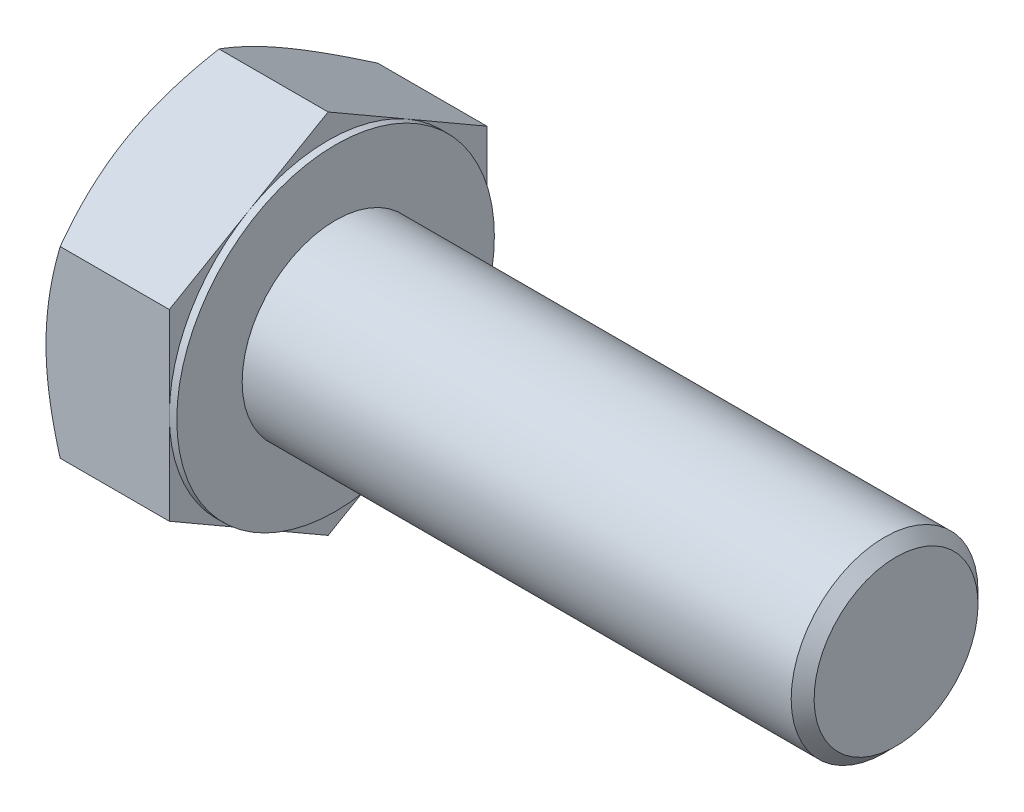
SolidWorks part; units mm, degrees
ref_plane "前基準面" through (0, 0, 0) normal (0, 0, 1) x (1, 0, 0)
ref_plane "上基準面" through (0, 0, 0) normal (0, 1, 0) x (1, 0, 0)
ref_plane "右基準面" through (0, 0, 0) normal (1, 0, 0) x (0, 0, -1)
ref_plane "平面1"
sketch "草圖1" plane through (0, 0, 0) normal (0, 0, 1) x (1, 0, 0)
  line L0 (-0.4001, 0) -> (30, 0)
  line L1 (30, 0) -> (30, 5)
  line L2 (30, 5) -> (3, 5)
  line L3 (3, 5) -> (2.3865, 5)
  line L4 (2.3865, 5) -> (0, 5)
  line L5 (0, 5) -> (0, 8.5)
  line L6 (0, 8.5) -> (-0.4001, 8.5)
  line L7 (-0.4001, 8.5) -> (-0.4001, 0)
  line L8 (30, 0) -> (-0.4001, 0) construction
revolve "本體" add sketch "草圖1" angle 360 about L8
cosmetic thread "裝飾螺紋線1" parameters "D1"=27, "D2"=8.344
sketch "草圖2" plane through (-0.4001, 0, 0) normal (-1, 0, 0) x (0, 0, 1)
  line L0 (0, 9.815) -> (8.5, 4.9075)
  line L1 (8.5, 4.9075) -> (8.5, -4.9075)
  line L2 (8.5, -4.9075) -> (0, -9.815)
  line L3 (0, -9.815) -> (-8.5, -4.9075)
  line L4 (-8.5, -4.9075) -> (-8.5, 4.9075)
  line L5 (-8.5, 4.9075) -> (0, 9.815)
  dimension "D1" = 17
extrude "頭" add sketch "草圖2" along normal blind 6.6
ref_plane "平面2"
sketch "草圖3" plane through (0, 0, 0) normal (0, 0, 1) x (1, 0, 0)
  line L0 (-7.0001, 8.5) -> (-7.0001, 9.815)
  line L1 (-7.0001, 9.815) -> (-6.2409, 9.815)
  line L2 (-6.2409, 9.815) -> (-7.0001, 8.5)
  line L3 (-8.3201, 0) -> (0.9199, 0) construction
  dimension "D1" = 30
  dimension "D2" = 90
revolve "螺紋" cut sketch "草圖3" angle 360 about L3
chamfer "倒角2" distance 0.6134 distance2 0.6136 1 edges at (30, 5, 0)
